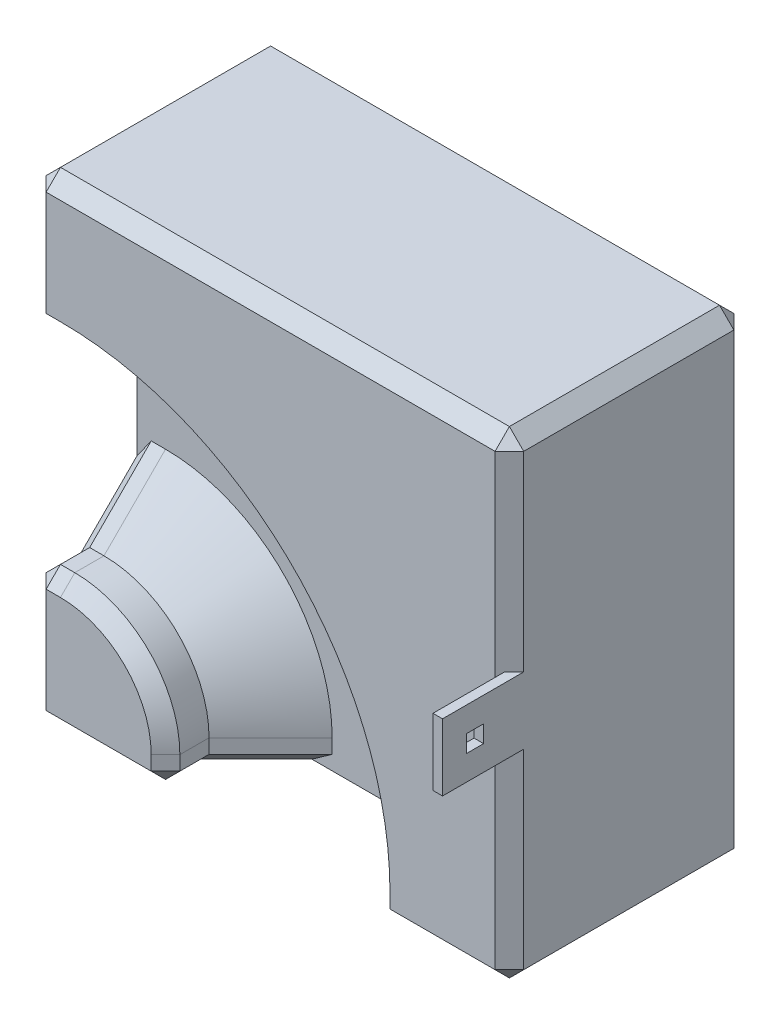
SolidWorks part; units mm, degrees
ref_plane "Front" through (0, 0, 0) normal (0, 0, 1) x (1, 0, 0)
ref_plane "Top" through (0, 0, 0) normal (0, 1, 0) x (1, 0, 0)
ref_plane "Right" through (0, 0, 0) normal (1, 0, 0) x (0, 0, -1)
sketch "Sketch1" plane through (0, 0, 0) normal (0, 0, 1) x (1, 0, 0)
  line L1 (0, 0) -> (50, 0)
  line L2 (0, 0) -> (0, 50)
  line L3 (0, 50) -> (50, 50)
  line L4 (50, 0) -> (50, 50)
  dimension "D1" = 50
extrude "Boss-Extrude1" add sketch "Sketch1" along normal blind 25
sketch "Sketch3" plane through (0, 0, 0) normal (0, -1, 0) x (1, 0, 0)
  line L0 (0, 25) -> (50, 25) construction
  line L1 (36, 29.5563) -> (29.5563, 36)
  line L2 (29.5563, 36) -> (20.4437, 36)
  line L3 (20.4437, 36) -> (14, 29.5563)
  line L4 (14, 29.5563) -> (14, 20.4437)
  line L5 (14, 20.4437) -> (20.4437, 14)
  line L6 (20.4437, 14) -> (29.5563, 14)
  line L7 (29.5563, 14) -> (36, 20.4437)
  line L8 (36, 20.4437) -> (36, 29.5563)
  circle A0 centre (25, 25) radius 11 construction
  dimension "D1" = 22
sketch "Sketch4" plane through (0, 0, 25) normal (0, 0, 1) x (1, 0, 0)
  line L0 (25, 0) -> (25, 3)
  line L1 (3, 25) -> (0, 25)
  line L2 (0, 50) -> (0, 0) construction
  arc A0 (25, 3) -> (3, 25) centre (3, 3) ccw
  dimension "D1" = 22
sweep "Cut-Sweep1" cut profiles "Sketch3" path "Sketch4"
chamfer "Chamfer1" distance 1.5 angle 45 28 edges at (36, 1.5, 25) (1.5, 36, 25) (26.3345, 26.3345, 25) (1.5, 14, 25) (10.7782, 10.7782, 25) (0, 25, 0) (25, 50, 0) (0, 50, 12.5) (0, 17.2218, 17.2218) (0, 14, 22.7218) (50, 50, 12.5) (50, 25, 0) (0, 32.7782, 17.2218) (0, 36, 22.7218) (0, 43, 25) (25, 50, 25) (50, 25, 25) (32.7782, 0, 17.2218) (36, 0, 22.7218) (43, 0, 25) (50, 0, 12.5) (25, 0, 0) (0, 0, 12.5) (17.2218, 0, 17.2218) (14, 0, 22.7218) (0, 7, 25) (7, 0, 25) (14, 1.5, 25)
sketch "Sketch5" plane through (0, 0, 25) normal (0, 0, 1) x (1, 0, 0)
  line L0 (50, 48.5) -> (50, 1.5) construction
  line L1 (50, 28.5) -> (49, 28.5)
  line L2 (50, 28.5) -> (50, 21.5)
  line L3 (50, 21.5) -> (49, 21.5)
  line L4 (49, 28.5) -> (49, 21.5)
  point P6 (50, 25)
  dimension "D1" = 7
  dimension "D2" = 1
extrude "Boss-Extrude2" add sketch "Sketch5" along normal blind 7 and the other way blind 10
sketch "Sketch6" plane through (50, 0, 0) normal (1, 0, 0) x (0, 0, -1)
  line L0 (-32, 25) -> (-29.5, 25) construction
  line L1 (-29.5, 25.9) -> (-27.7, 25.9)
  line L2 (-29.5, 25.9) -> (-29.5, 24.1)
  line L3 (-29.5, 24.1) -> (-27.7, 24.1)
  line L4 (-27.7, 25.9) -> (-27.7, 24.1)
  line L5 (-32, 21.5) -> (-32, 28.5) construction
  dimension "D1" = 2.5
  dimension "D2" = 1.8
extrude "Cut-Extrude1" cut sketch "Sketch6" against normal blind 7
